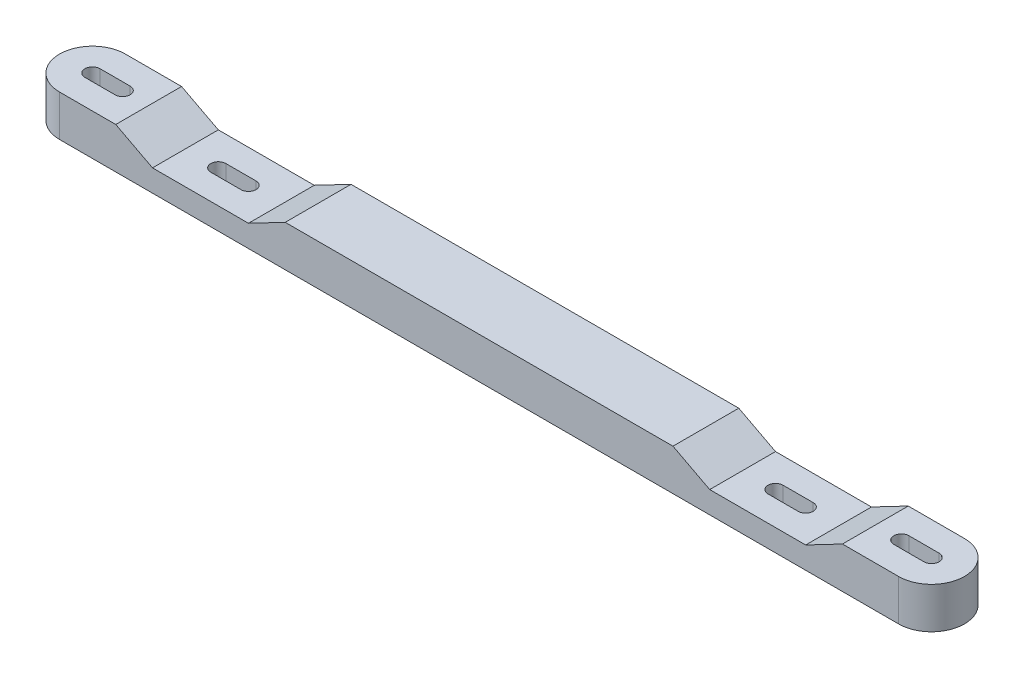
SolidWorks part; units mm, degrees
ref_plane "Front Plane" through (0, 0, 0) normal (0, 0, 1) x (1, 0, 0)
ref_plane "Top Plane" through (0, 0, 0) normal (0, 1, 0) x (1, 0, 0)
ref_plane "Right Plane" through (0, 0, 0) normal (1, 0, 0) x (0, 0, -1)
sketch "Sketch1" plane through (0, 0, 0) normal (0, 1, 0) x (1, 0, 0)
  line L0 (-153, 101.6) -> (-142, 101.6) construction
  line L1 (-153, 101.6) -> (153, 101.6) construction
  line L2 (-153, 101.6) -> (-153, -101.6) construction
  line L3 (-153, -101.6) -> (153, -101.6) construction
  line L4 (153, 101.6) -> (153, -101.6) construction
  line L5 (-153, 101.6) -> (153, -101.6) construction
  line L6 (-153, -101.6) -> (153, 101.6) construction
  line L7 (-153, 104.35) -> (-142, 104.35)
  line L8 (-153, 98.85) -> (-142, 98.85)
  line L9 (-107.1, 101.6) -> (-96.1, 101.6) construction
  line L10 (-107.1, 104.35) -> (-96.1, 104.35)
  line L11 (-107.1, 98.85) -> (-96.1, 98.85)
  line L12 (96.1, 101.6) -> (107.1, 101.6) construction
  line L13 (96.1, 104.35) -> (107.1, 104.35)
  line L14 (96.1, 98.85) -> (107.1, 98.85)
  line L15 (153, 101.6) -> (142, 101.6) construction
  line L16 (153, 98.85) -> (142, 98.85)
  line L17 (153, 104.35) -> (142, 104.35)
  line L18 (153, -101.6) -> (142, -101.6) construction
  line L19 (153, -104.35) -> (142, -104.35) construction
  line L20 (153, -98.85) -> (142, -98.85) construction
  line L21 (96.1, -101.6) -> (107.1, -101.6) construction
  line L22 (96.1, -98.85) -> (107.1, -98.85) construction
  line L23 (96.1, -104.35) -> (107.1, -104.35) construction
  line L24 (-107.1, -101.6) -> (-96.1, -101.6) construction
  line L25 (-107.1, -98.85) -> (-96.1, -98.85) construction
  line L26 (-107.1, -104.35) -> (-96.1, -104.35) construction
  line L27 (-153, -101.6) -> (-142, -101.6) construction
  line L28 (-153, -98.85) -> (-142, -98.85) construction
  line L29 (-153, -104.35) -> (-142, -104.35) construction
  line L30 (-101.6, 101.6) -> (-101.6, -101.6) construction
  line L31 (101.6, 101.6) -> (101.6, -101.6) construction
  line L32 (-153, 101.6) -> (153, 101.6) construction
  line L33 (-153, 113.6) -> (153, 113.6)
  line L34 (-153, 89.6) -> (153, 89.6)
  line L35 (-111.6, 89.6) -> (-111.6, -89.6) construction
  line L38 (-91.6, 89.6) -> (-91.6, -89.6) construction
  line L41 (-153, -101.6) -> (153, -101.6) construction
  line L42 (-153, -89.6) -> (153, -89.6) construction
  line L43 (-153, -113.6) -> (153, -113.6) construction
  line L44 (91.6, 89.6) -> (91.6, -89.6) construction
  line L45 (113.3339, 89.6) -> (113.3339, -89.6) construction
  arc A0 (-153, 104.35) -> (-153, 98.85) centre (-153, 101.6) ccw
  arc A1 (-142, 98.85) -> (-142, 104.35) centre (-142, 101.6) ccw
  arc A2 (-107.1, 104.35) -> (-107.1, 98.85) centre (-107.1, 101.6) ccw
  arc A3 (-96.1, 98.85) -> (-96.1, 104.35) centre (-96.1, 101.6) ccw
  arc A4 (96.1, 104.35) -> (96.1, 98.85) centre (96.1, 101.6) ccw
  arc A5 (107.1, 98.85) -> (107.1, 104.35) centre (107.1, 101.6) ccw
  arc A6 (153, 98.85) -> (153, 104.35) centre (153, 101.6) ccw
  arc A7 (142, 104.35) -> (142, 98.85) centre (142, 101.6) ccw
  arc A8 (153, -104.35) -> (153, -98.85) centre (153, -101.6) ccw construction
  arc A9 (142, -98.85) -> (142, -104.35) centre (142, -101.6) ccw construction
  arc A10 (96.1, -98.85) -> (96.1, -104.35) centre (96.1, -101.6) ccw construction
  arc A11 (107.1, -104.35) -> (107.1, -98.85) centre (107.1, -101.6) ccw construction
  arc A12 (-107.1, -98.85) -> (-107.1, -104.35) centre (-107.1, -101.6) ccw construction
  arc A13 (-96.1, -104.35) -> (-96.1, -98.85) centre (-96.1, -101.6) ccw construction
  arc A14 (-153, -98.85) -> (-153, -104.35) centre (-153, -101.6) ccw construction
  arc A15 (-142, -104.35) -> (-142, -98.85) centre (-142, -101.6) ccw construction
  arc A16 (-153, 113.6) -> (-153, 89.6) centre (-153, 101.6) ccw
  arc A17 (153, 89.6) -> (153, 113.6) centre (153, 101.6) ccw
  arc A22 (-153, -89.6) -> (-153, -113.6) centre (-153, -101.6) ccw construction
  arc A23 (153, -113.6) -> (153, -89.6) centre (153, -101.6) ccw construction
  point P0 (0, 0)
  point P7 (-147.5, 101.6)
  point P12 (-101.6, 101.6)
  point P19 (101.6, 101.6)
  point P26 (147.5, 101.6)
  point P32 (147.5, -101.6)
  point P38 (101.6, -101.6)
  point P45 (-101.6, -101.6)
  point P52 (-147.5, -101.6)
  point P62 (0, 101.6)
  point P77 (-165, 101.6)
  point P78 (165, 101.6)
  point P79 (0, -101.6)
  dimension "D4" = 2.75
  dimension "D7" = 12
  dimension "D8" = 10
  dimension "D12" = 330
  dimension "D1" = 203.2
  dimension "D2" = 295
  dimension "D3" = 11
  dimension "D5" = 101.6
  dimension "D6" = 101.6
  dimension "D9" = 10
  dimension "D10" = 10
  dimension "D11" = 11.7339
extrude "Boss-Extrude2" add sketch "Sketch1" along normal blind 15
sketch "Sketch4" plane through (0, 0, -89.6) normal (0, 0, 1) x (1, 0, 0)
  line L1 (-153, 15) -> (153, 15) construction
  line L3 (-105, 0) -> (-165, 0) construction
  line L4 (-165, 0) -> (-165, 10) construction
  line L6 (-153, 0) -> (153, 0) construction
  line L7 (165, 10) -> (165, 0) construction
  line L8 (165, 0) -> (105, 0) construction
  line L9 (-132.5, 15) -> (-119.1, 8)
  line L11 (-119.1, 8) -> (-84.1, 8)
  line L12 (119.1, 8) -> (132.5, 15)
  line L13 (132.5, 15) -> (70.7, 15)
  line L14 (-84.1, 8) -> (-70.7, 15)
  line L15 (70.7, 15) -> (84.1, 8)
  line L16 (84.1, 8) -> (119.1, 8)
  line L17 (-70.7, 15) -> (-132.5, 15)
  line L18 (-132.5, 15) -> (132.5, 15) construction
  line L20 (-165, 10) -> (-105, 10) construction
  line L21 (-105, 10) -> (-105, 0) construction
  line L22 (105, 0) -> (105, 10) construction
  line L23 (105, 10) -> (165, 10) construction
  line L24 (-165, 10) -> (-105, 0) construction
  line L25 (105, 0) -> (165, 10) construction
  point P3 (-101.6, 8)
  point P22 (0, 15)
  dimension "D1" = 35
  dimension "D2" = 35
  dimension "D3" = 5
  dimension "D4" = 8
  dimension "D5" = 5
  dimension "D6" = 265
  dimension "D7" = 101.6
  dimension "D9" = 60
extrude "Cut-Extrude3" cut sketch "Sketch4" against normal through all
